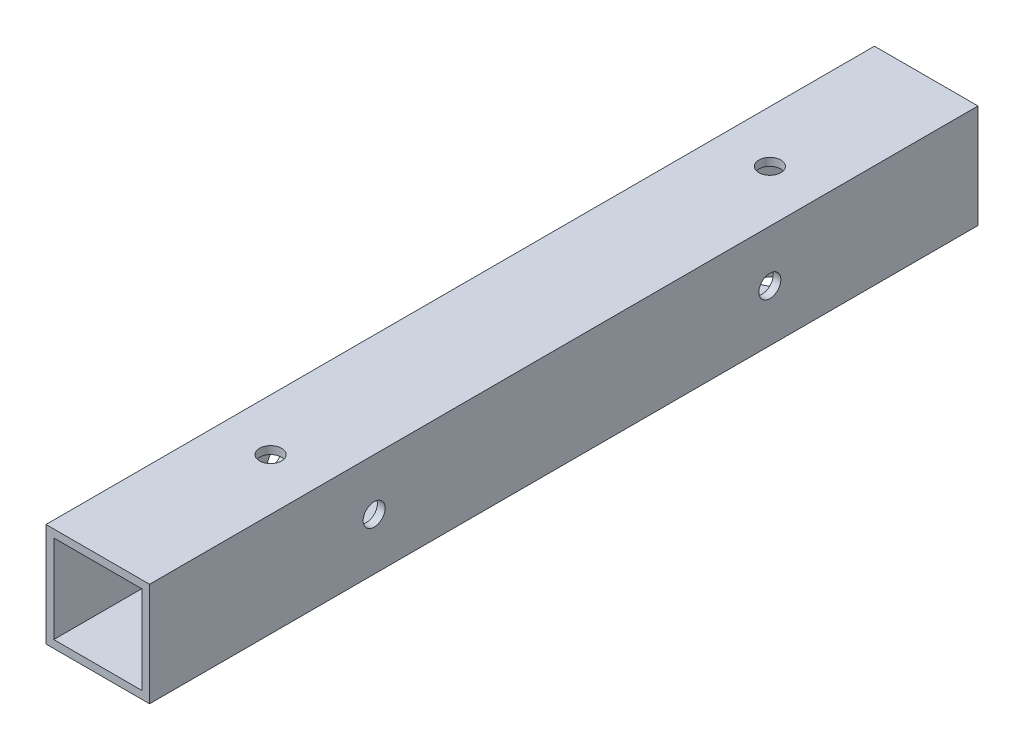
SolidWorks part; units mm, degrees
ref_plane "Front Plane" through (0, 0, 0) normal (0, 0, 1) x (1, 0, 0)
ref_plane "Top Plane" through (0, 0, 0) normal (0, 1, 0) x (1, 0, 0)
ref_plane "Right Plane" through (0, 0, 0) normal (1, 0, 0) x (0, 0, -1)
sketch "Sketch1" plane through (0, 0, 0) normal (0, 0, 1) x (1, 0, 0)
  line L0 (-8.5, -8.5) -> (8.5, -8.5)
  line L1 (-10, -10) -> (10, -10)
  line L2 (-10, -10) -> (-10, 10)
  line L3 (-10, 10) -> (10, 10)
  line L4 (10, -10) -> (10, 10)
  line L5 (-10, -10) -> (10, 10) construction
  line L6 (-10, 10) -> (10, -10) construction
  line L7 (8.5, -8.5) -> (8.5, 8.5)
  line L8 (-8.5, 8.5) -> (8.5, 8.5)
  line L9 (-8.5, -8.5) -> (-8.5, 8.5)
  point P0 (0, 0)
  dimension "D1" = 20
  dimension "D3" = 20
  dimension "D2" = 1.5
extrude "Boss-Extrude1" add sketch "Sketch1" against normal blind 160
sketch "Sketch2" plane through (0, 10, 0) normal (0, 1, 0) x (1, 0, 0)
  line L0 (10, 0) -> (-10, 0) construction
  line L1 (10, 160) -> (-10, 160) construction
  circle A0 centre (0, 33.375) radius 2.125
  circle A1 centre (0, 129.8) radius 2.125
  dimension "D1" = 4.25
  dimension "D3" = 4.25
  dimension "D2" = 33.375
  dimension "D4" = 30.2
extrude "Cut-Extrude1" cut sketch "Sketch2" against normal through all
sketch "Sketch3" plane through (-10, 0, 0) normal (-1, 0, 0) x (0, 0, 1)
  line L0 (-160, 10) -> (-160, -10) construction
  circle A0 centre (-43.375, 0) radius 2.125
  circle A1 centre (-119.8, 0) radius 2.125
  dimension "D1" = 4.25
  dimension "D3" = 4.25
  dimension "D2" = 43.375
  dimension "D4" = 40.2
extrude "Cut-Extrude2" cut sketch "Sketch3" against normal through all
